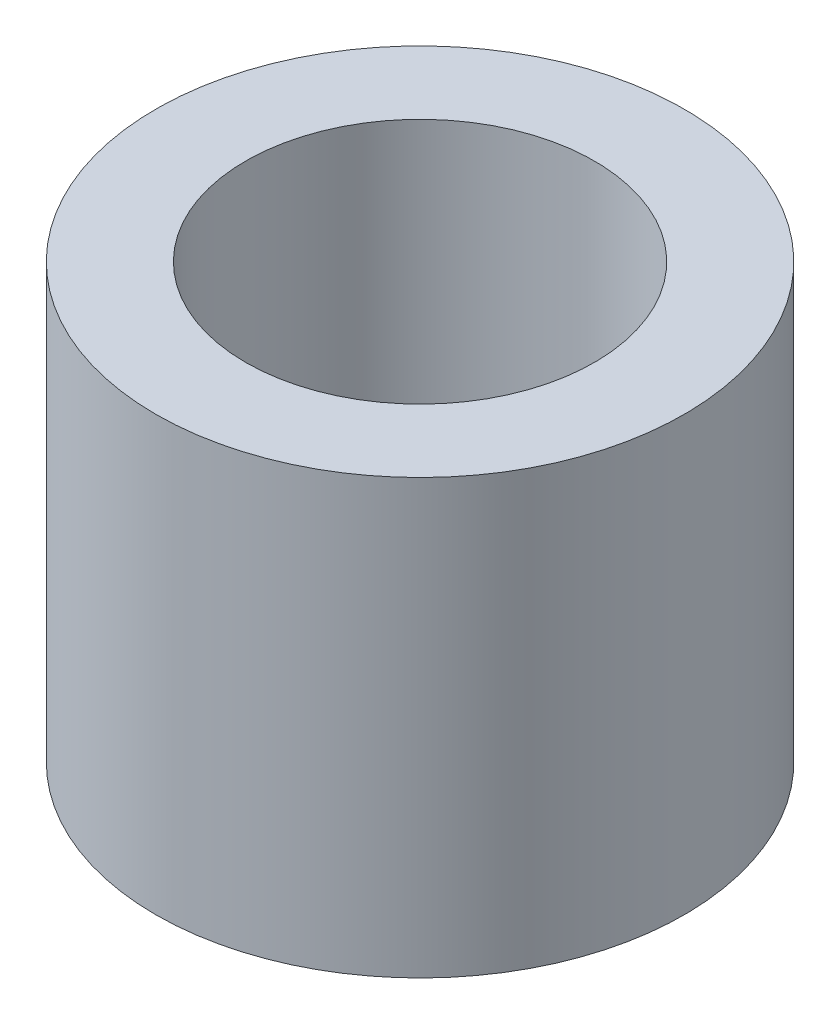
SolidWorks part; units mm, degrees
ref_plane "前视基准面" through (0, 0, 0) normal (0, 0, 1) x (1, 0, 0)
ref_plane "上视基准面" through (0, 0, 0) normal (0, 1, 0) x (1, 0, 0)
ref_plane "右视基准面" through (0, 0, 0) normal (1, 0, 0) x (0, 0, -1)
sketch "草图1" plane through (0, 0, 0) normal (0, 1, 0) x (1, 0, 0)
  circle A0 centre (0, 0) radius 1.65
  circle A1 centre (0, 0) radius 2.5
  dimension "D1" = 3.3
extrude "凸台-拉伸1" add sketch "草图1" along normal blind 4.1
